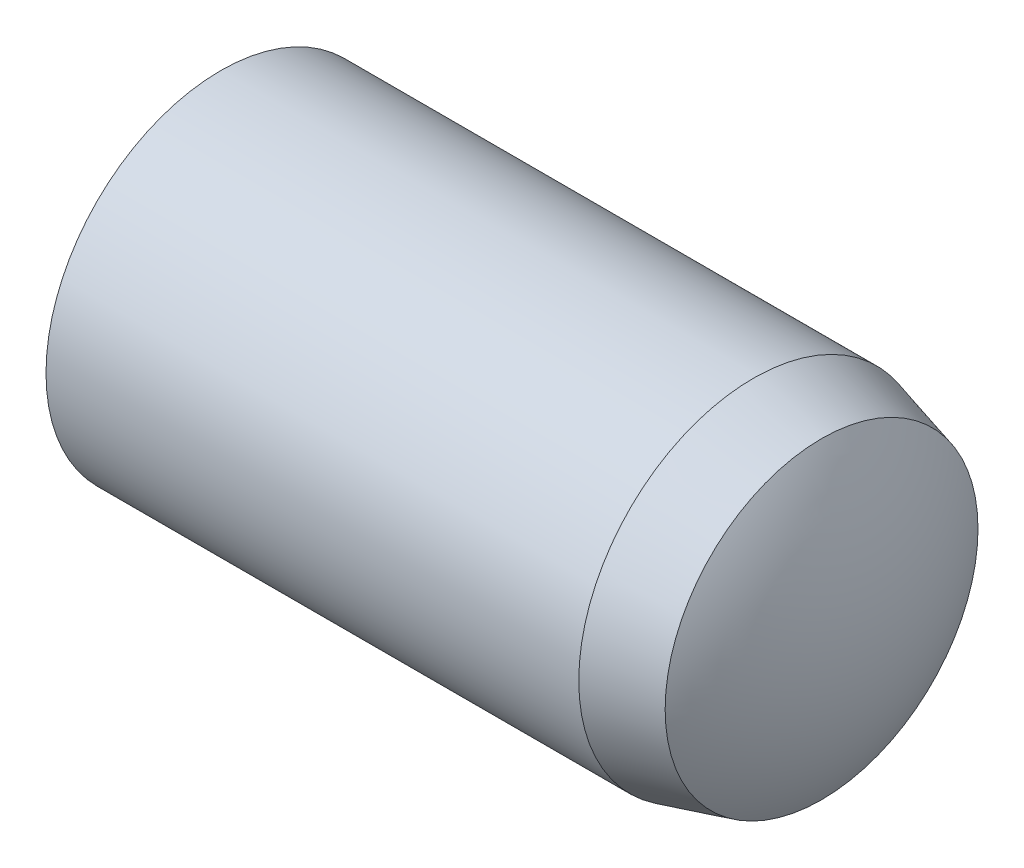
SolidWorks part; units mm, degrees
ref_plane "Front Plane" through (0, 0, 0) normal (0, 0, 1) x (1, 0, 0)
ref_plane "Top Plane" through (0, 0, 0) normal (0, 1, 0) x (1, 0, 0)
ref_plane "Right Plane" through (0, 0, 0) normal (1, 0, 0) x (0, 0, -1)
sketch "Sketch1" plane through (0, 0, 0) normal (0, 0, 1) x (1, 0, 0)
  line L0 (-8, 0) -> (8, 0) construction
  line L1 (8, 4) -> (8, -4) construction
  line L2 (-8, 4) -> (-8, -4) construction
  line L3 (5.4, 4) -> (5.4, -4) construction
  line L4 (-6.8, 4) -> (-6.8, -4) construction
  line L5 (-8, 0) -> (-6.8, 0) construction
  line L6 (8, 0) -> (5.4, 0) construction
  line L7 (6.96, 4) -> (6.96, -4) construction
  dimension "Dia" = 8
  dimension "Length" = 16
  dimension "D1" = 2.6
  dimension "D2" = 1.2
  dimension "D3" = 1.56
sketch "Sketch2" plane through (0, 0, 0) normal (1, 0, 0) x (0, 0, -1)
  circle A0 centre (0, 0) radius 4
extrude "Extrude1" add sketch "Sketch2" against normal up to vertex (8 mm away) and the other way up to vertex (8 mm away) up to point (-8, 0, 0) other way up to point (8, 0, 0)
sketch "Sketch5" plane through (0, 0, 0) normal (0, 0, 1) x (1, 0, 0)
  line L0 (5.4, 4) -> (5.4, 4.5)
  line L1 (5.4, 4.5) -> (8.5, 4.5)
  line L2 (8.5, 4.5) -> (8.5, 0)
  line L3 (8, 0) -> (8.5, 0)
  line L5 (-6.8, 4) -> (-6.8, 4.5)
  line L6 (-6.8, 4.5) -> (-8.5, 4.5)
  line L7 (-8.5, 4.5) -> (-8.5, 0)
  line L8 (5.4, 4) -> (6.96, 3.582)
  line L10 (-8, 0) -> (-8.5, 0)
  line L11 (-8, 4) -> (-8, -4) construction
  line L13 (5.4, 4) -> (5.4, -4) construction
  line L15 (-8, 0) -> (8, 0) construction
  line L16 (6.96, 4) -> (6.96, -4) construction
  line L17 (8, 4) -> (8, -4) construction
  arc A0 (6.96, 3.582) -> (8, 0) centre (1.3114, 0) cw
  arc A1 (-6.8, 4) -> (-8, 0) centre (-0.7333, 0) ccw
  dimension "D1" = 15
  dimension "D2" = 0.5
revolve "Cut-Revolve1" cut sketch "Sketch5" angle 360 about L0
equation "\"D1@Sketch1\" = \"Dia@Sketch1\"*.325"
equation "\"D2@Sketch1\" = \"Dia@Sketch1\"*.15"
equation "\"D3@Sketch1\" = \"D1@Sketch1\"*.6"
